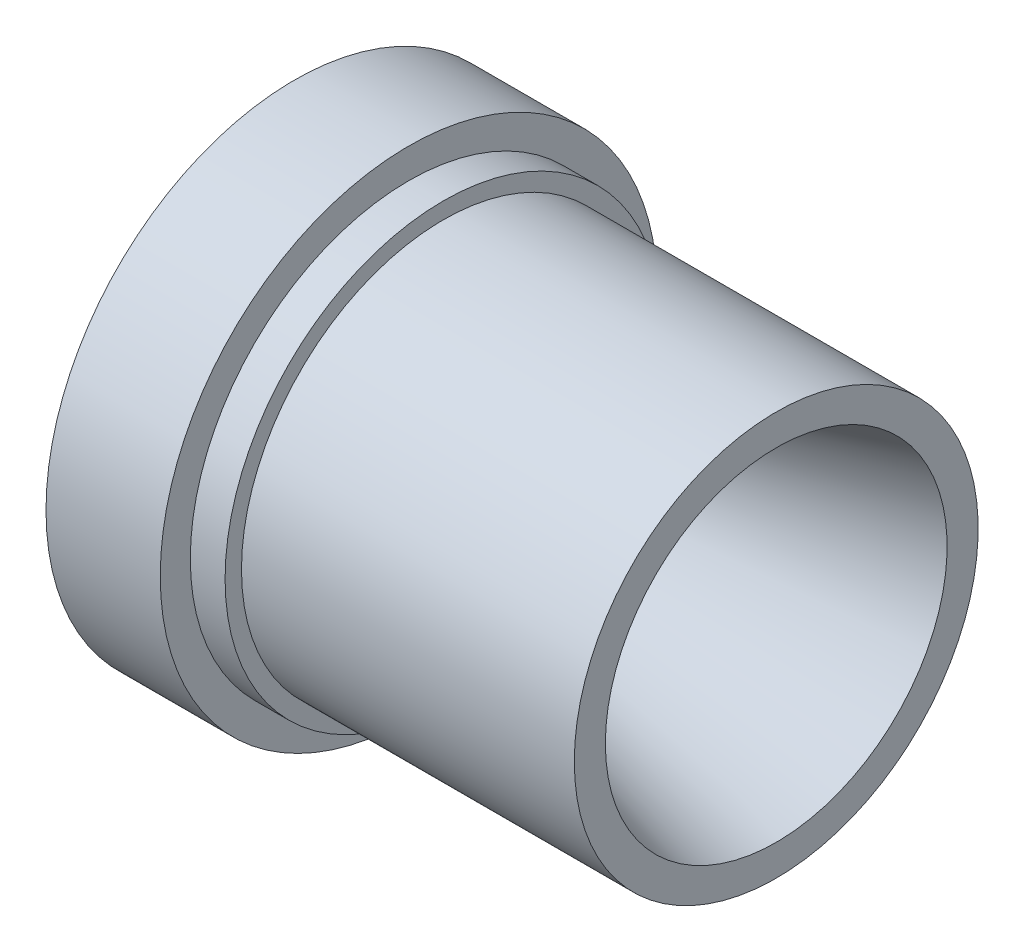
SolidWorks part; units mm, degrees
material "Rubber"
ref_plane "Front Plane" through (0, 0, 0) normal (0, 0, 1) x (1, 0, 0)
ref_plane "Top Plane" through (0, 0, 0) normal (0, 1, 0) x (1, 0, 0)
ref_plane "Right Plane" through (0, 0, 0) normal (1, 0, 0) x (0, 0, -1)
sketch "Sketch1" plane through (0, 0, 0) normal (0, 0, 1) x (1, 0, 0)
  line L0 (0, 0) -> (23.0396, 0) construction
  line L1 (0, 0) -> (-7.3703, 0) construction
  line L2 (0, 3.6957) -> (18.8166, 8.7376)
  line L3 (18.8166, 8.7376) -> (18.8166, 10.3251)
  line L4 (18.8166, 10.3251) -> (1.7986, 10.3251)
  line L5 (1.7986, 10.3251) -> (1.7986, 11.1633)
  line L6 (1.7986, 11.1633) -> (0.0206, 11.1633)
  line L7 (0.0206, 11.1633) -> (0.0206, 12.7)
  line L8 (0.0206, 12.7) -> (-5.8214, 12.7)
  line L9 (-5.8214, 12.7) -> (-5.8214, 7.9375)
  line L10 (-5.8214, 7.9375) -> (-1.5796, 3.6957)
  line L11 (-1.5796, 3.6957) -> (0, 3.6957)
  line L12 (0, 0) -> (0, 3.6957) construction
  dimension "D1" = 7.3914
  dimension "D2" = 15
  dimension "D3" = 17.4752
  dimension "D4" = 20.6502
  dimension "D5" = 22.3266
  dimension "D6" = 25.4
  dimension "D7" = 45
  dimension "D8" = 7.62
  dimension "D9" = 5.842
  dimension "D10" = 24.638
  dimension "D11" = 15.875
  dimension "D12" = 1.5796
revolve "Revolve1" add sketch "Sketch1" angle 360 about L0
